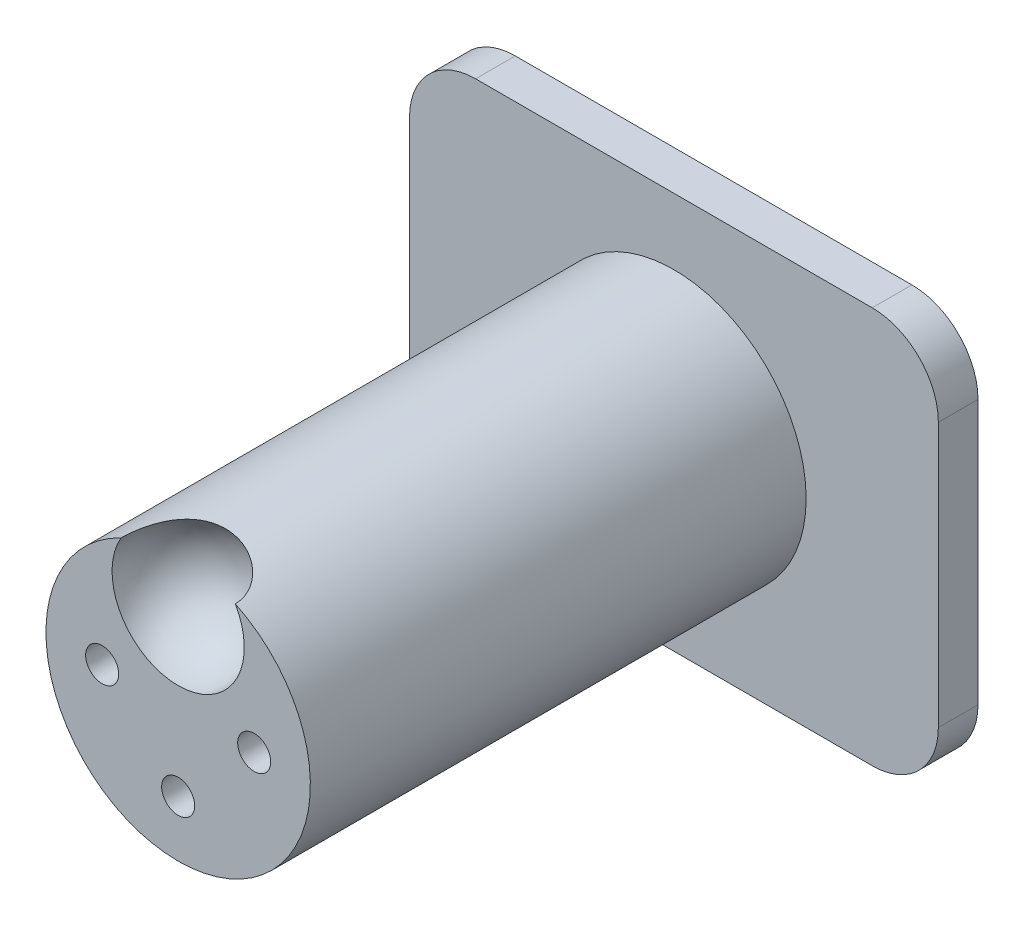
SolidWorks part; units mm, degrees
ref_plane "前视" through (0, 0, 0) normal (0, 0, 1) x (1, 0, 0)
ref_plane "上视" through (0, 0, 0) normal (0, 1, 0) x (1, 0, 0)
ref_plane "右视" through (0, 0, 0) normal (1, 0, 0) x (0, 0, -1)
sketch "草图1" plane through (0, 0, 0) normal (0, 0, 1) x (1, 0, 0)
  line L1 (30.0422, -35) -> (-49.9578, -35)
  line L2 (30.0422, -35) -> (30.0422, 25)
  line L3 (30.0422, 25) -> (-49.9578, 25)
  line L4 (-49.9578, -35) -> (-49.9578, 25)
extrude "凸台-拉伸1" add sketch "草图1" along normal blind 6
sketch "草图2" plane through (0, 0, 6) normal (0, 0, 1) x (1, 0, 0)
  circle A0 centre (-9.9578, -5) radius 20
extrude "凸台-拉伸2" add sketch "草图2" along normal blind 75
sketch "草图4" plane through (0, 0, 81) normal (0, 0, 1) x (1, 0, 0)
  line L1 (-9.9578, -2) -> (-9.9578, 18)
  arc A3 (-9.9578, -2) -> (-9.9578, 18) centre (-9.9578, 8) ccw
sketch "草图7" plane through (0, 0, 81) normal (0, 0, 1) x (1, 0, 0)
  circle A3 centre (-9.9578, -16.5) radius 2.5
  circle A7 centre (-21.4578, -5) radius 2.5
  circle A9 centre (1.5422, -5) radius 2.5
extrude "切除-拉伸2" cut sketch "草图7" against normal blind 20
fillet "圆角1" radius 10 4 edges at (-49.9578, -35, 3) (30.0422, -35, 3) (-49.9578, 25, 3) (30.0422, 25, 3)
revolve "切除-旋转1" cut sketch "草图4" angle 180 about L1
